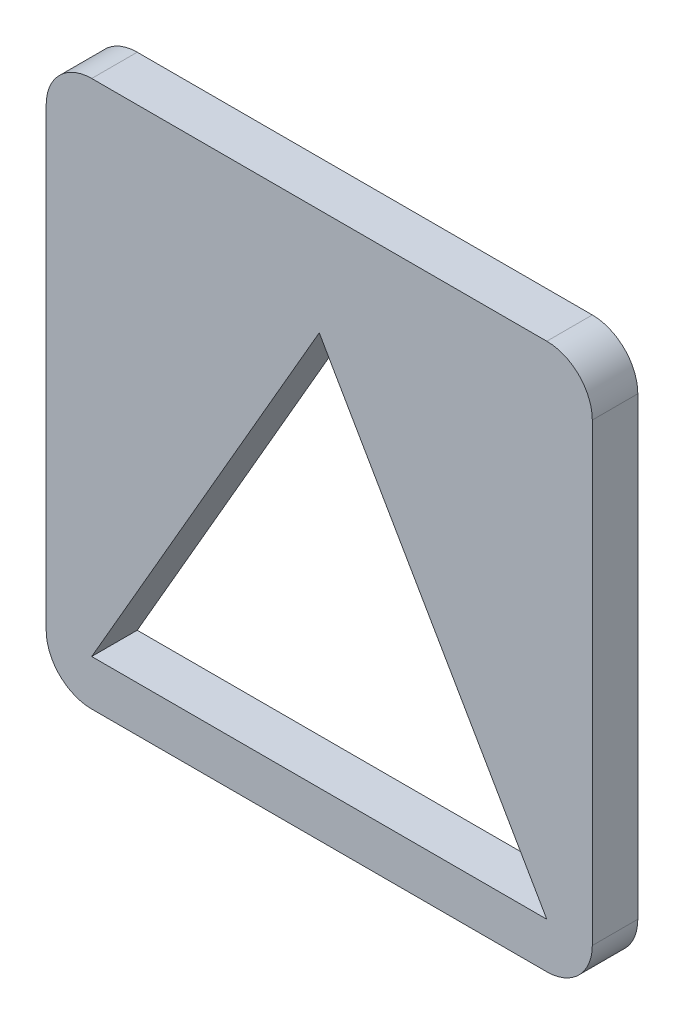
SolidWorks part; units mm, degrees
ref_plane "Front Plane" through (0, 0, 0) normal (0, 0, 1) x (1, 0, 0)
ref_plane "Top Plane" through (0, 0, 0) normal (0, 1, 0) x (1, 0, 0)
ref_plane "Right Plane" through (0, 0, 0) normal (1, 0, 0) x (0, 0, -1)
sketch "Sketch1" plane through (0, 0, 0) normal (0, 0, 1) x (1, 0, 0)
  line L1 (-50, 60) -> (50, 60)
  line L2 (-60, 50) -> (-60, -50)
  line L3 (-50, -60) -> (50, -60)
  line L4 (60, 50) -> (60, -50)
  line L5 (-60, 60) -> (60, -60) construction
  line L6 (-60, -60) -> (60, 60) construction
  arc A0 (-60, -50) -> (-50, -60) centre (-50, -50) ccw
  arc A1 (50, -60) -> (60, -50) centre (50, -50) ccw
  arc A2 (50, 60) -> (60, 50) centre (50, 50) cw
  arc A3 (-50, 60) -> (-60, 50) centre (-50, 50) ccw
  point P0 (0, 0)
  dimension "D3" = 10
  dimension "D1" = 120
  dimension "D2" = 120
extrude "Boss-Extrude1" add sketch "Sketch1" along normal blind 10 contours A3 L2 A0 L3 A1 L4 A2 L1
sketch "Sketch2" plane through (0, 0, 10) normal (0, 0, 1) x (1, 0, 0)
  line L0 (0, 0) -> (0, 40) construction
  line L1 (-50, 50) -> (50, 50) construction
  line L2 (-50, 50) -> (-50, -50) construction
  line L3 (-50, -50) -> (50, -50) construction
  line L4 (50, 50) -> (50, -50) construction
  line L5 (-50, 50) -> (50, -50) construction
  line L6 (-50, -50) -> (50, 50) construction
  line L7 (0, 40) -> (-40, 40) construction
  line L8 (-40, 40) -> (-40, 0) construction
  line L9 (-40, 0) -> (0, 0) construction
  line L11 (0, 20) -> (-20, 20) construction
  line L12 (-20, 40) -> (-20, 20) construction
  circle A0 centre (0, 40) radius 4 construction
  circle A1 centre (0, 20) radius 4 construction
  circle A2 centre (0, 0) radius 4 construction
  circle A3 centre (-20, 20) radius 4 construction
  circle A4 centre (-20, 40) radius 4 construction
  circle A5 centre (-40, 40) radius 4 construction
  circle A6 centre (0, 0) radius 4 construction
  circle A7 centre (20, 0) radius 4 construction
  circle A8 centre (40, 0) radius 4 construction
  circle A9 centre (40, 20) radius 4 construction
  circle A10 centre (40, 40) radius 4 construction
  circle A11 centre (20, 20) radius 4 construction
  circle A12 centre (0, 0) radius 4 construction
  circle A13 centre (0, -20) radius 4 construction
  circle A14 centre (0, -40) radius 4 construction
  circle A15 centre (20, -40) radius 4 construction
  circle A16 centre (40, -40) radius 4 construction
  circle A17 centre (20, -20) radius 4 construction
  circle A18 centre (0, 0) radius 4
  circle A19 centre (-20, 0) radius 4 construction
  circle A20 centre (-40, 0) radius 4 construction
  circle A21 centre (-40, -20) radius 4 construction
  circle A22 centre (-40, -40) radius 4 construction
  circle A23 centre (-20, -20) radius 4 construction
  point P0 (0, 0)
  point P55 (0, 0)
  dimension "D4" = 8
  dimension "D1" = 100
  dimension "D2" = 100
  dimension "D3" = 40
  dimension "D5" = 4
sketch "Sketch3" plane through (0, 0, 10) normal (0, 0, 1) x (1, 0, 0)
  line L0 (-50, -50) -> (50, -50)
  line L1 (50, -50) -> (0, 36.6025)
  line L2 (0, 36.6025) -> (-50, -50)
  dimension "D1" = 100
  dimension "D2" = 100
extrude "Cut-Extrude1" cut sketch "Sketch3" against normal blind 10
